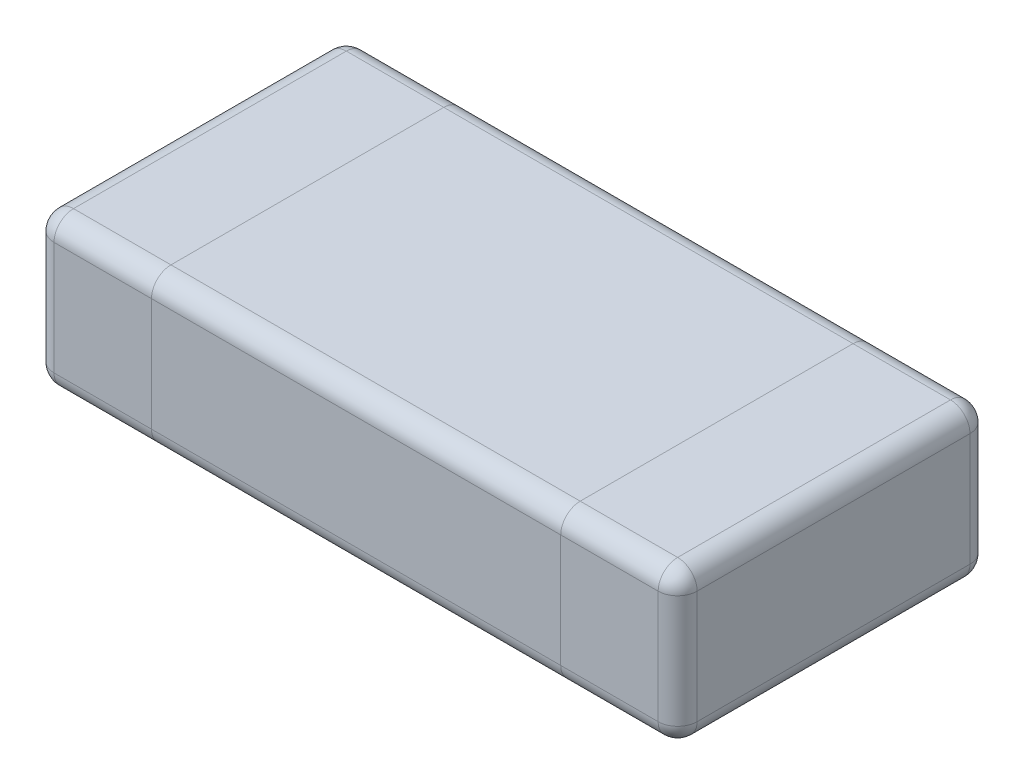
SolidWorks part; units mm, degrees
ref_plane "Alzado" through (0, 0, 0) normal (0, 0, 1) x (1, 0, 0)
ref_plane "Planta" through (0, 0, 0) normal (0, 1, 0) x (1, 0, 0)
ref_plane "Vista lateral" through (0, 0, 0) normal (1, 0, 0) x (0, 0, -1)
sketch "Croquis1" plane through (0, 0, 0) normal (0, 1, 0) x (1, 0, 0)
  line L1 (-1.05, -0.8) -> (1.05, -0.8)
  line L2 (-1.05, -0.8) -> (-1.05, 0.8)
  line L3 (-1.05, 0.8) -> (1.05, 0.8)
  line L4 (1.05, -0.8) -> (1.05, 0.8)
  line L5 (-1.05, -0.8) -> (1.05, 0.8) construction
  line L6 (-1.05, 0.8) -> (1.05, -0.8) construction
  point P0 (0, 0)
  dimension "D1" = 2.1
  dimension "D2" = 1.6
extrude "Saliente-Extruir1" add sketch "Croquis1" along normal blind 0.78
sketch "Croquis3" plane through (0, 0, 0) normal (0, 1, 0) x (1, 0, 0)
  line L0 (1.05, 0.8) -> (1.65, 0.8)
  line L1 (1.65, 0.8) -> (1.65, -0.8)
  line L2 (1.65, -0.8) -> (1.05, -0.8)
  line L3 (1.05, -0.8) -> (1.05, 0.8) construction
  line L4 (1.05, -0.8) -> (1.05, 0.8)
  line L5 (0, 1.3421) -> (0, -1.4057) construction
  line L6 (-1.05, -0.8) -> (-1.05, 0.8)
  line L7 (-1.65, -0.8) -> (-1.05, -0.8)
  line L8 (-1.65, 0.8) -> (-1.65, -0.8)
  line L9 (-1.05, 0.8) -> (-1.65, 0.8)
  dimension "D1" = 0.6
extrude "Saliente-Extruir3" add sketch "Croquis3" along normal blind 0.78 separate body
fillet "Redondeo2" radius 0.1 4 edges at (0, 0, 0.8) (0, 0.78, 0.8) (0, 0, -0.8) (0, 0.78, -0.8)
fillet "Redondeo4" radius 0.1 8 edges at (1.65, 0.39, 0.8) (1.65, 0.78, 0) (1.65, 0.39, -0.8) (1.65, 0, 0) (1.35, 0, 0.8) (1.35, 0.78, 0.8) (1.35, 0.78, -0.8) (1.35, 0, -0.8)
fillet "Redondeo5" radius 0.1 8 edges at (-1.65, 0.39, -0.8) (-1.65, 0.78, 0) (-1.65, 0.39, 0.8) (-1.65, 0, 0) (-1.35, 0, -0.8) (-1.35, 0.78, -0.8) (-1.35, 0, 0.8) (-1.35, 0.78, 0.8)
